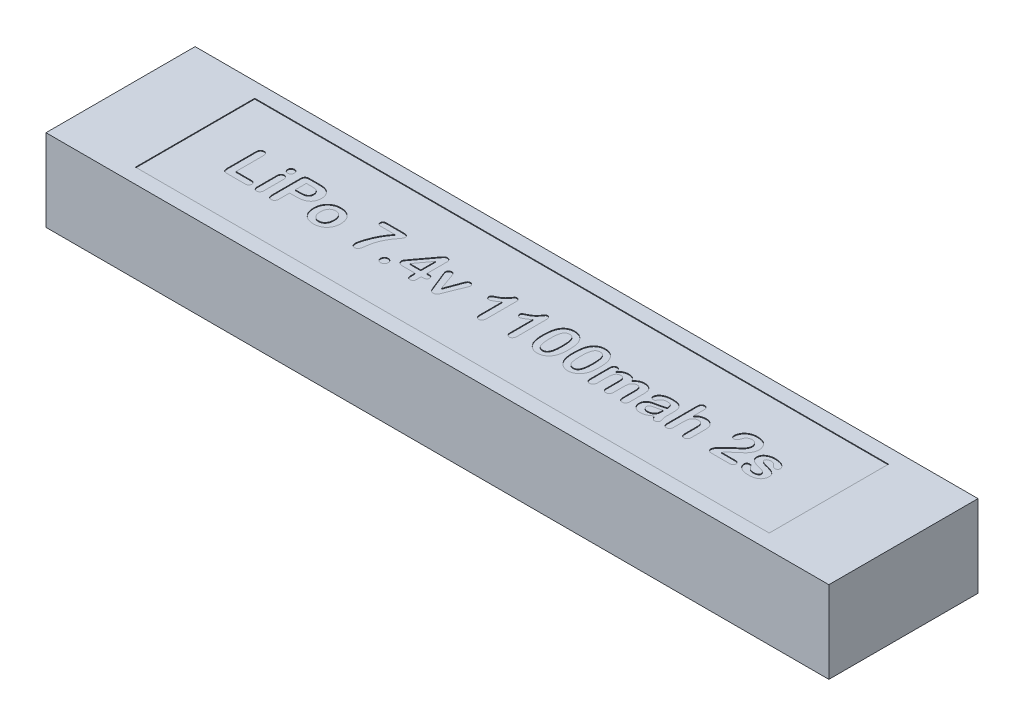
SolidWorks part; units mm, degrees
ref_plane "Plano frontal" through (0, 0, 0) normal (0, 0, 1) x (1, 0, 0)
ref_plane "Plano superior" through (0, 0, 0) normal (0, 1, 0) x (1, 0, 0)
ref_plane "Plano direito" through (0, 0, 0) normal (1, 0, 0) x (0, 0, -1)
sketch "Esboço1" plane through (0, 0, 0) normal (0, 1, 0) x (1, 0, 0)
  line L1 (0, 0) -> (105, 0)
  line L2 (0, 0) -> (0, 20)
  line L3 (0, 20) -> (105, 20)
  line L4 (105, 0) -> (105, 20)
  dimension "D1" = 105
  dimension "D2" = 20
extrude "Ressalto-extrusão1" add sketch "Esboço1" along normal blind 11
ref_plane "Escrita" through (0, 11, 0) normal (0, 1, 0) x (1, 0, 0)
sketch "Esboço2" plane through (0, 11, 0) normal (0, 1, 0) x (1, 0, 0)
  line L0 (105, 20) -> (0, 20) construction
  line L1 (10, 2) -> (95, 2)
  line L2 (10, 2) -> (10, 18)
  line L3 (10, 18) -> (95, 18)
  line L4 (95, 2) -> (95, 18)
  line L5 (0, 0) -> (105, 0) construction
  line L6 (105, 0) -> (105, 20) construction
  line L7 (0, 20) -> (0, 0) construction
  dimension "D1" = 2
  dimension "D2" = 2
  dimension "D3" = 10
  dimension "D4" = 10
extrude "Corte-extrusão1" cut sketch "Esboço2" against normal blind 0.1
sketch "Esboço3" plane through (0, 11, 0) normal (0, 1, 0) x (1, 0, 0)
  line L0 (15.67, 7.5) -> (90.0601, 7.5) construction
  line L1 (0, 0) -> (105, 0) construction
  line L5 (0, 20) -> (0, 0) construction
  text T0 "LiPo 7.4v 1100mah 2s" font "Arial Rounded MT Bold" height in points 20
  dimension "D1" = 15.67
  dimension "D2" = 7.5
extrude "Corte-extrusão2" cut sketch "Esboço3" against normal blind 0.2
